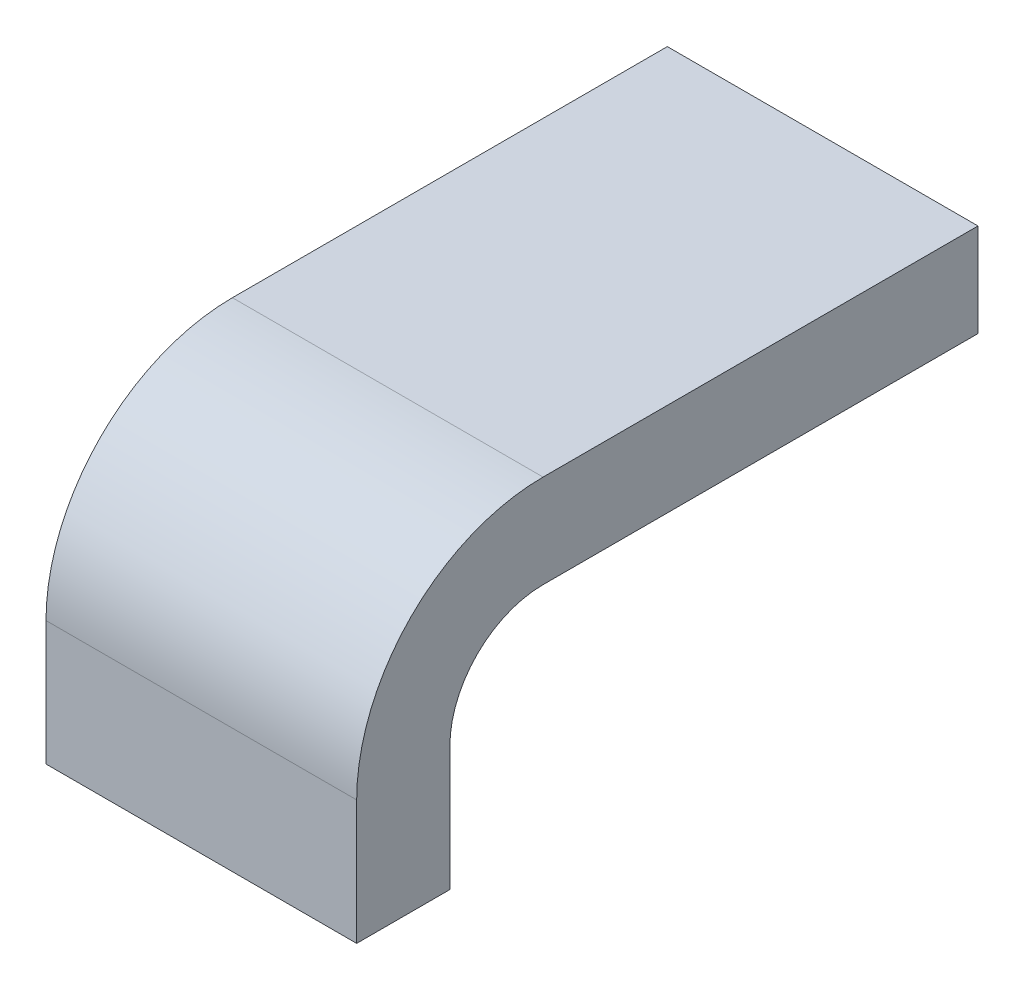
SolidWorks part; units mm, degrees
ref_plane "前基準面" through (0, 0, 0) normal (0, 0, 1) x (1, 0, 0)
ref_plane "上基準面" through (0, 0, 0) normal (0, 1, 0) x (1, 0, 0)
ref_plane "右基準面" through (0, 0, 0) normal (1, 0, 0) x (0, 0, -1)
sketch "草圖2" plane through (0, 0, 0) normal (1, 0, 0) x (0, 0, -1)
  line L0 (5.2607, 5.2844) -> (-8.7393, 5.2844)
  line L1 (-14.7393, -0.7156) -> (-14.7393, -4.7156)
  line L2 (-14.7393, -4.7156) -> (-11.7393, -4.7156)
  line L3 (-11.7393, -4.7156) -> (-11.7393, -0.7156)
  line L4 (-8.7393, 2.2844) -> (5.2607, 2.2844)
  line L5 (5.2607, 2.2844) -> (5.2607, 5.2844)
  arc A0 (-8.7393, 5.2844) -> (-14.7393, -0.7156) centre (-8.7393, -0.7156) ccw
  arc A1 (-8.7393, 2.2844) -> (-11.7393, -0.7156) centre (-8.7393, -0.7156) ccw
  point P8 (-14.7393, 5.2844)
  dimension "D4" = 6
  dimension "D5" = 3
  dimension "D1" = 20
  dimension "D2" = 10
  dimension "D3" = 3
extrude "填料-伸長1" add sketch "草圖2" along normal mid plane 10 contours L0 A0 L1 L2 L3 A1 L4 L5
